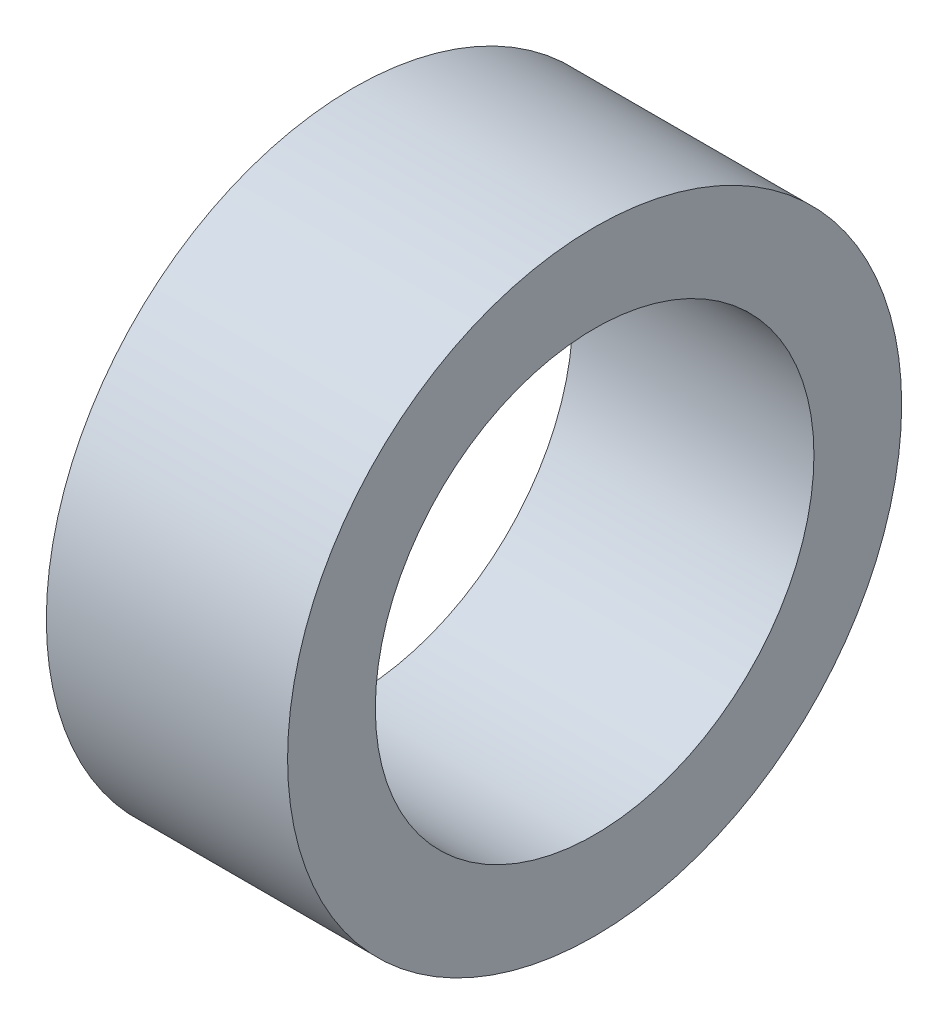
SolidWorks part; units mm, degrees
ref_plane "Front Plane" through (0, 0, 0) normal (0, 0, 1) x (1, 0, 0)
ref_plane "Top Plane" through (0, 0, 0) normal (0, 1, 0) x (1, 0, 0)
ref_plane "Right Plane" through (0, 0, 0) normal (1, 0, 0) x (0, 0, -1)
sketch "Sketch1" plane through (0, 0, 0) normal (0, 0, 1) x (1, 0, 0)
  line L0 (21, 7) -> (21, 5)
  line L1 (21, 5) -> (26.5, 5)
  line L2 (26.5, 5) -> (26.5, 7)
  line L3 (26.5, 7) -> (21, 7)
  line L4 (21, 0) -> (26.5, 0) construction
revolve "Revolve1" add sketch "Sketch1" angle 360 about L4
